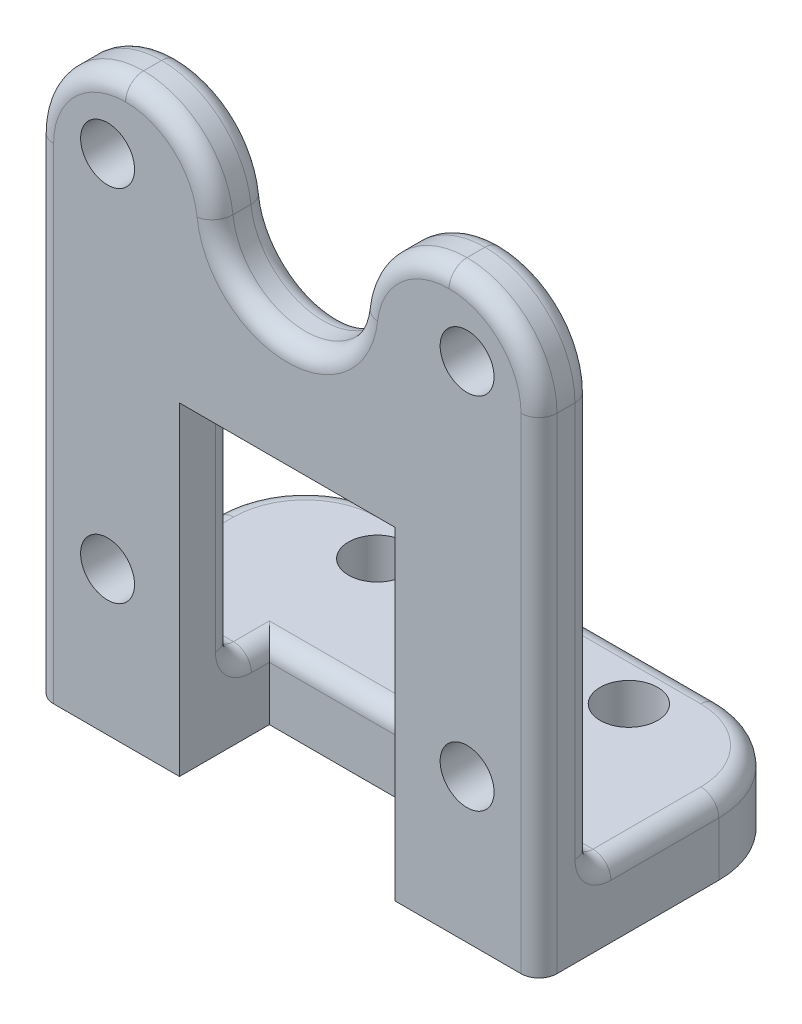
SolidWorks part; units mm, degrees
ref_plane "前视基准面" through (0, 0, 0) normal (0, 0, 1) x (1, 0, 0)
ref_plane "上视基准面" through (0, 0, 0) normal (0, 1, 0) x (1, 0, 0)
ref_plane "右视基准面" through (0, 0, 0) normal (1, 0, 0) x (0, 0, -1)
sketch "草图1" plane through (0, 0, 0) normal (0, 0, 1) x (1, 0, 0)
  line L0 (6, -14) -> (14, -14)
  line L1 (-14, 14) -> (-0.6344, 14)
  line L2 (-14, 14) -> (-14, -14)
  line L3 (-14, -14) -> (-6, -14)
  line L4 (14, 14) -> (14, -14)
  line L5 (-14, 14) -> (14, -14) construction
  line L6 (-14, -14) -> (14, 14) construction
  line L7 (-6, 0) -> (6, 0)
  line L8 (-6, 0) -> (-6, -14)
  line L10 (6, 0) -> (6, -14)
  line L11 (0.6344, 14) -> (14, 14)
  circle A0 centre (-10, 10) radius 1.5
  circle A1 centre (10, 10) radius 1.5
  circle A2 centre (10, -10) radius 1.5
  circle A3 centre (-10, -10) radius 1.5
  arc A4 (-0.6344, 14) -> (0.6344, 14) centre (0, 10) ccw
  point P0 (0, 0)
  point P17 (0, 0)
  dimension "D3" = 3
  dimension "D6" = 8.1
  dimension "D1" = 28
  dimension "D2" = 28
  dimension "D4" = 10
  dimension "D7" = 14
  dimension "D8" = 12
  dimension "D9" = 6
  dimension "D5" = 4
extrude "凸台-拉伸2" add sketch "草图1" along normal blind 3
sketch "草图2" plane through (0, -14, 0) normal (0, -1, 0) x (1, 0, 0)
  line L0 (6, 3) -> (14, 3)
  line L1 (-14, 3) -> (-6, 3)
  line L2 (-14, 3) -> (-14, -12)
  line L3 (-14, -12) -> (14, -12)
  line L4 (14, 3) -> (14, -12)
  line L6 (-6, 3) -> (-6, -2)
  line L7 (-6, -2) -> (6, -2)
  line L8 (6, 3) -> (6, -2)
  dimension "D1" = 15
  dimension "D2" = 28
  dimension "D3" = 5
  dimension "D4" = 12
extrude "凸台-拉伸3" add sketch "草图2" along normal blind 4
sketch "草图3" plane through (0, -14, 0) normal (0, 1, 0) x (1, 0, 0)
  line L0 (0, -1000) -> (0, 49000) construction
  line L1 (-14, 12) -> (14, 12) construction
  circle A0 centre (-7, 9) radius 1.6
  circle A1 centre (7, 9) radius 1.6
  dimension "D1" = 3.2
  dimension "D2" = 7
  dimension "D3" = 3
extrude "切除-拉伸1" cut sketch "草图3" against normal blind 5
fillet "圆角1" radius 5 6 edges at (-0.6344, 14, 1.5) (0.6344, 14, 1.5) (-14, 14, 1.5) (14, 14, 1.5) (-14, -16, -12) (14, -16, -12)
fillet "圆角2" radius 1 22 edges at (0, 5.95, 0) (5.6601, 12.7258, 0) (-5.6601, 12.7258, 0) (8.9973, 14, 0) (-8.9973, 14, 0) (12.5355, 12.5355, 0) (-12.5355, 12.5355, 0) (14, -2.5, 0) (-14, -2.5, 0) (12.5355, -14, -10.5355) (14, -14, -3.5) (10, -14, 0) (6, -14, -1) (0, -14, -2) (-6, -14, -1) (-10, -14, 0) (-14, -14, -3.5) (-12.5355, -14, -10.5355) (0, -14, -12) (-6, -7, 0) (6, -7, 0) (0, 0, 0)
fillet "圆角3" radius 1 9 edges at (14, -4.5, 3) (12.5355, 12.5355, 3) (8.9973, 14, 3) (5.6601, 12.7258, 3) (0, 5.95, 3) (-14, -4.5, 3) (-12.5355, 12.5355, 3) (-8.9973, 14, 3) (-5.6601, 12.7258, 3)
